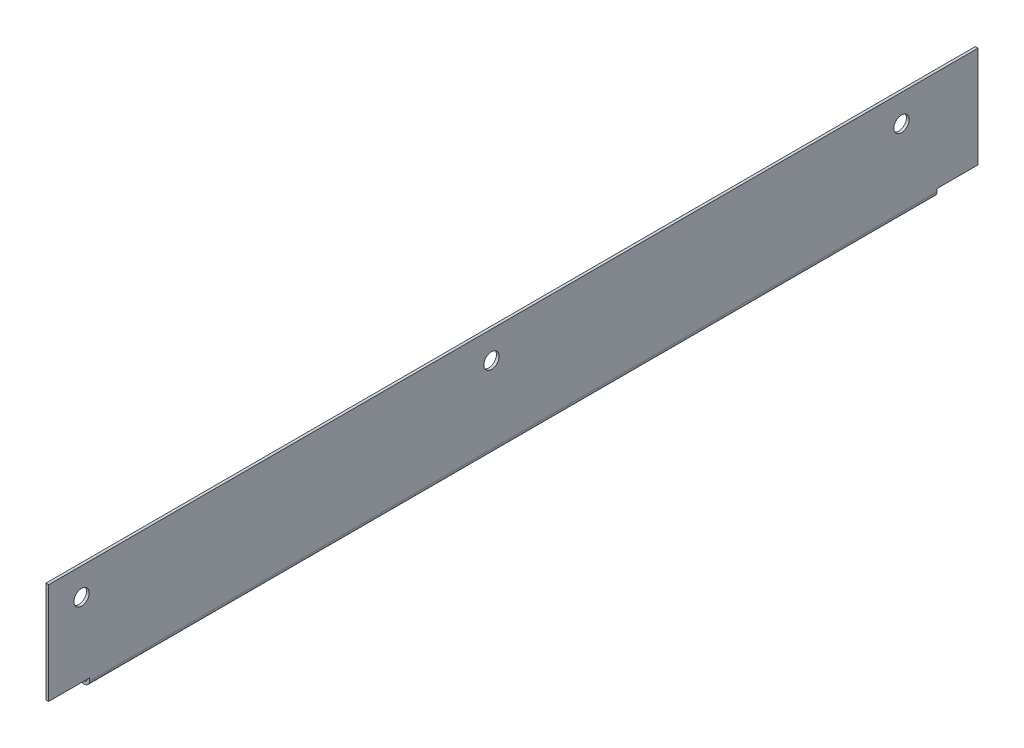
SolidWorks part; units mm, degrees
ref_plane "Спереди" through (0, 0, 0) normal (0, 0, 1) x (1, 0, 0)
ref_plane "Сверху" through (0, 0, 0) normal (0, 1, 0) x (1, 0, 0)
ref_plane "Справа" through (0, 0, 0) normal (1, 0, 0) x (0, 0, -1)
sketch "Эскиз1" plane through (0, 0, 0) normal (0, 0, 1) x (1, 0, 0)
  line L0 (0, 0) -> (0, 42.8354) construction
  line L1 (0, 0) -> (34, 0) construction
  line L2 (-2, 0) -> (-15, 0)
  line L3 (0, 2) -> (0, 40)
  line L4 (-2, 1) -> (-15, 1)
  line L5 (-1, 2) -> (-1, 40)
  line L6 (-1, 40) -> (0, 40)
  line L7 (-15, 1) -> (-15, 0)
  line L8 (-1, 1) -> (-15, 1) construction
  line L9 (-1, 1) -> (-1, 40) construction
  line L10 (0, 0) -> (0, 40) construction
  line L11 (0, 0) -> (-15, 0) construction
  arc A0 (-2, 1) -> (-1, 2) centre (-2, 2) ccw
  arc A1 (0, 2) -> (-2, 0) centre (-2, 2) cw
  dimension "D1" = 40
  dimension "D4" = 1
  dimension "D5" = 2
  dimension "D2" = 15
  dimension "D3" = 1
extrude "Вытянуть1" add sketch "Эскиз1" against normal blind 340
sketch "Эскиз2" plane through (0, 0, 0) normal (1, 0, 0) x (0, 0, -1)
  line L0 (-10.0095, 30) -> (347.9915, 30) construction
  line L3 (340, 0) -> (0, 0) construction
  line L4 (340, 2) -> (340, 40) construction
  circle A0 centre (12, 30) radius 2.8
  circle A1 centre (162, 30) radius 2.8
  circle A2 centre (312, 30) radius 2.8
  dimension "D2" = 28
  dimension "D3" = 150
  dimension "D4" = 150
  dimension "D5" = 5.6
  dimension "D1" = 30
extrude "Вырез-Вытянуть1" cut sketch "Эскиз2" against normal blind 340
sketch "Эскиз3" plane through (0, 0, 0) normal (0, -1, 0) x (1, 0, 0)
  line L0 (-9, 0) -> (-9, 64.9266) construction
  line L3 (-15, -340) -> (-15, 0) construction
  line L5 (-15, 0) -> (-2, 0) construction
  circle A0 centre (-9, -240) radius 2.15
  circle A1 centre (-9, -170) radius 2.15
  circle A2 centre (-9, -100) radius 2.15
  circle A3 centre (-9, -30) radius 2.15
  dimension "D2" = 30
  dimension "D3" = 4.3
  dimension "D4" = 210
  dimension "D5" = 70
  dimension "D6" = 70
  dimension "D1" = 6
extrude "Вырез-Вытянуть2" cut sketch "Эскиз3" against normal blind 340
sketch "Эскиз4" plane through (0, 0, 0) normal (0, -1, 0) x (1, 0, 0)
  line L1 (-12.3496, 325) -> (25.2737, 325)
  line L2 (-12.3496, 325) -> (-12.3496, 345.6559)
  line L3 (-12.3496, 345.6559) -> (25.2737, 345.6559)
  line L4 (25.2737, 325) -> (25.2737, 345.6559)
  line L5 (-15, 0) -> (-2, 0) construction
  line L6 (-17.2738, 0) -> (25.2737, 0)
  line L7 (-17.2738, 0) -> (-17.2738, -15)
  line L8 (-17.2738, -15) -> (25.2737, -15)
  line L9 (25.2737, 0) -> (25.2737, -15)
  line L11 (-15, -340) -> (19.5096, -340)
  line L12 (-15, -340) -> (-15, -325)
  line L13 (-15, -325) -> (19.5096, -325)
  line L14 (19.5096, -340) -> (19.5096, -325)
  dimension "D2" = 15
  dimension "D3" = 15
extrude "Вырез-Вытянуть3" cut sketch "Эскиз4" against normal blind 3
